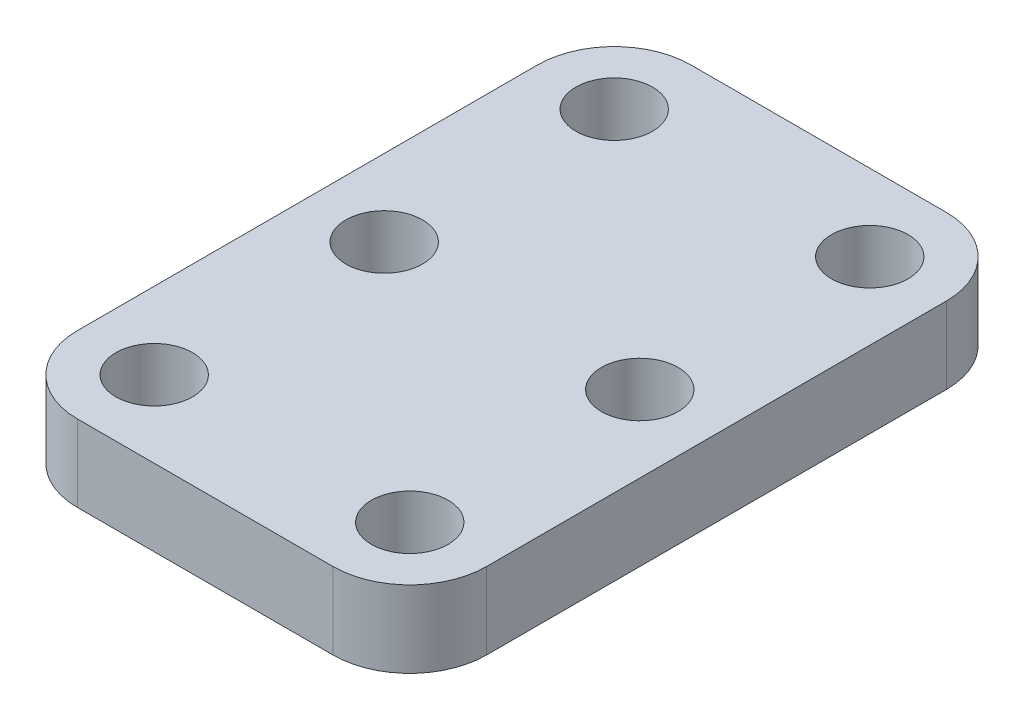
SolidWorks part; units mm, degrees
ref_plane "Plano frontal" through (0, 0, 0) normal (0, 0, 1) x (1, 0, 0)
ref_plane "Plano superior" through (0, 0, 0) normal (0, 1, 0) x (1, 0, 0)
ref_plane "Plano direito" through (0, 0, 0) normal (1, 0, 0) x (0, 0, -1)
sketch "Esboço1" plane through (0, 0, 0) normal (0, 1, 0) x (1, 0, 0)
  line L1 (0, 0) -> (80, 0)
  line L2 (0, 0) -> (0, 120)
  line L3 (0, 120) -> (80, 120)
  line L4 (80, 0) -> (80, 120)
  dimension "D1" = 80
  dimension "D2" = 120
extrude "Ressalto-extrusão1" add sketch "Esboço1" along normal blind 15
fillet "Filete1" radius 15 4 edges at (0, 7.5, -120) (0, 7.5, 0) (80, 7.5, -120) (80, 7.5, 0)
sketch "Esboço2" plane through (0, 15, 0) normal (0, 1, 0) x (1, 0, 0)
  line L0 (65, 120) -> (15, 120) construction
  line L1 (0, 105) -> (0, 15) construction
  circle A0 centre (15, 105) radius 7.5
  circle A1 centre (65, 105) radius 7.5
  circle A2 centre (65, 60) radius 7.5
  circle A3 centre (65, 15) radius 7.5
  circle A4 centre (15, 60) radius 7.5
  circle A5 centre (15, 15) radius 7.5
  dimension "D1" = 15
  dimension "D2" = 15
  dimension "D3" = 15
  dimension "D4" = 2
  dimension "D5" = 3
extrude "Corte-extrusão1" cut sketch "Esboço2" against normal through all
